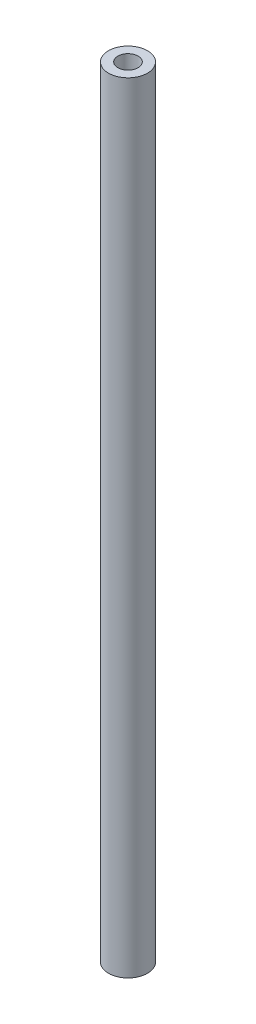
SolidWorks part; units mm, degrees
ref_plane "Front Plane" through (0, 0, 0) normal (0, 0, 1) x (1, 0, 0)
ref_plane "Top Plane" through (0, 0, 0) normal (0, 1, 0) x (1, 0, 0)
ref_plane "Right Plane" through (0, 0, 0) normal (1, 0, 0) x (0, 0, -1)
sketch "Sketch1" plane through (0, 0, 0) normal (0, 1, 0) x (1, 0, 0)
  circle A0 centre (0, 0) radius 5
  dimension "D1" = 10
extrude "Boss-Extrude1" add sketch "Sketch1" along normal blind 200
sketch "Sketch2" plane through (0, 0, 0) normal (0, -1, 0) x (1, 0, 0)
  circle A0 centre (0, 0) radius 2.6
  dimension "D1" = 5.2
extrude "Cut-Extrude1" cut sketch "Sketch2" against normal blind 10
sketch "Sketch3" plane through (0, 200, 0) normal (0, 1, 0) x (1, 0, 0)
  circle A0 centre (0, 0) radius 2.6
  dimension "D1" = 5.2
extrude "Cut-Extrude2" cut sketch "Sketch3" against normal blind 10
